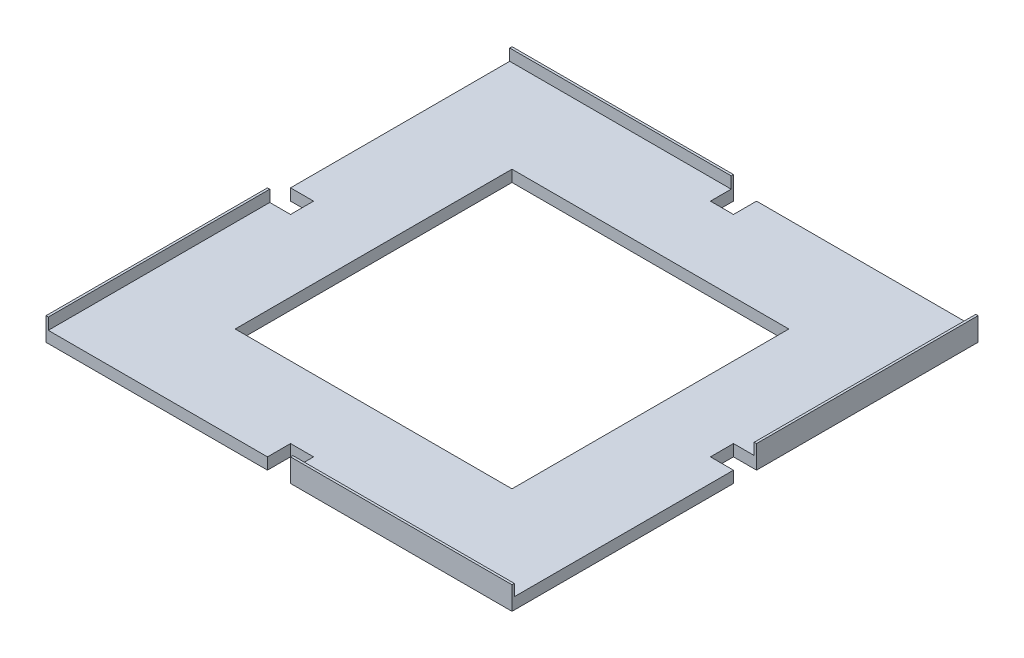
SolidWorks part; units mm, degrees
ref_plane "Front Plane" through (0, 0, 0) normal (0, 0, 1) x (1, 0, 0)
ref_plane "Top Plane" through (0, 0, 0) normal (0, 1, 0) x (1, 0, 0)
ref_plane "Right Plane" through (0, 0, 0) normal (1, 0, 0) x (0, 0, -1)
sketch "Sketch1" plane through (0, 0, 0) normal (0, 1, 0) x (1, 0, 0)
  line L0 (-91, 0) -> (91, 0) construction
  line L1 (101, -101) -> (5, -101)
  line L2 (101, -101) -> (101, -5)
  line L3 (101, 101) -> (5, 101)
  line L4 (-101, -101) -> (-101, -5)
  line L5 (101, -101) -> (-101, 101) construction
  line L6 (101, 101) -> (-101, -101) construction
  line L7 (-60, -60) -> (60, -60)
  line L8 (-60, -60) -> (-60, 60)
  line L9 (-60, 60) -> (60, 60)
  line L10 (60, -60) -> (60, 60)
  line L11 (-60, -60) -> (60, 60) construction
  line L12 (-60, 60) -> (60, -60) construction
  line L13 (0, 91) -> (0, -91) construction
  line L14 (-5, 101) -> (-5, 91)
  line L15 (-101, -5) -> (-91, -5)
  line L17 (-101, 5) -> (-91, 5)
  line L18 (-91, -5) -> (-91, 5)
  line L19 (101, 5) -> (101, 101)
  line L20 (-5, -101) -> (-101, -101)
  line L22 (5, 101) -> (5, 91)
  line L23 (-5, 91) -> (5, 91)
  line L24 (101, 5) -> (91, 5)
  line L26 (101, -5) -> (91, -5)
  line L27 (91, 5) -> (91, -5)
  line L28 (5, -101) -> (5, -91)
  line L30 (-5, -101) -> (-5, -91)
  line L31 (5, -91) -> (-5, -91)
  line L32 (-101, 5) -> (-101, 101)
  line L33 (-5, 101) -> (-101, 101)
  line L34 (-55, 0) -> (55, 0) construction
  point P0 (0, 0)
  point P6 (0, 0)
  point P32 (81.5341, 5)
  point P34 (0, 0)
  point P35 (10.5646, -91)
  point P36 (0, 0)
  dimension "D1" = 202
  dimension "D2" = 202
  dimension "D3" = 120
  dimension "D4" = 120
  dimension "D5" = 10
  dimension "D6" = 10
  dimension "D7" = 4
extrude "Boss-Extrude1" add sketch "Sketch1" along normal blind 5
sketch "Sketch2" plane through (0, 5, 0) normal (0, 1, 0) x (1, 0, 0)
  line L0 (101, -101) -> (101, -5) construction
  line L1 (5, -101) -> (101, -101)
  line L2 (5, -101) -> (5, -100)
  line L3 (5, -100) -> (101, -100)
  line L4 (101, -101) -> (101, -100)
  line L5 (-101, -5) -> (-100, -5)
  line L6 (-100, -5) -> (-100, -101)
  line L7 (-101, -5) -> (-101, -101)
  line L8 (-101, -101) -> (-100, -101)
  line L9 (-5, 101) -> (-5, 100)
  line L10 (-5, 100) -> (-101, 100)
  line L11 (-5, 101) -> (-101, 101)
  line L12 (-101, 101) -> (-101, 100)
  line L13 (101, 5) -> (100, 5)
  line L14 (100, 5) -> (100, 101)
  line L15 (101, 5) -> (101, 101)
  line L16 (101, 101) -> (100, 101)
  point P22 (0, 0)
  dimension "D1" = 1
  dimension "D2" = 4
extrude "Boss-Extrude2" add sketch "Sketch2" along normal blind 5
